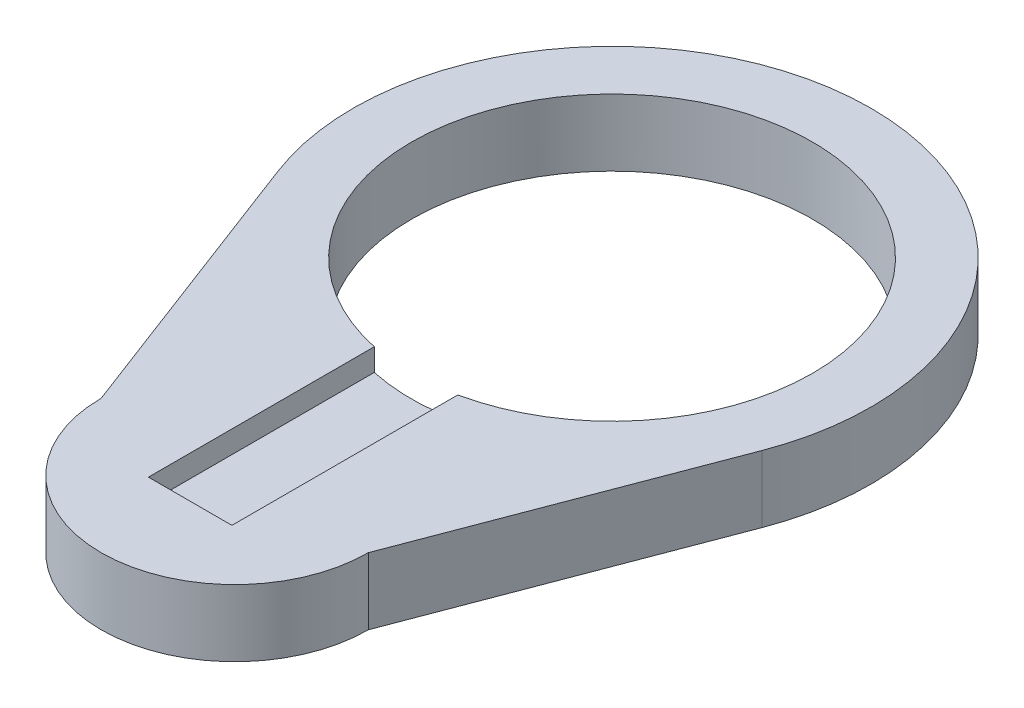
SolidWorks part; units mm, degrees
ref_plane "Front Plane" through (0, 0, 0) normal (0, 0, 1) x (1, 0, 0)
ref_plane "Top Plane" through (0, 0, 0) normal (0, 1, 0) x (1, 0, 0)
ref_plane "Right Plane" through (0, 0, 0) normal (1, 0, 0) x (0, 0, -1)
sketch "Sketch1" plane through (0, 0, 0) normal (0, 1, 0) x (1, 0, 0)
  line L0 (-21.7354, 25.6357) -> (-12, 0)
  line L1 (0, 120.2958) -> (0, -44.3308) construction
  line L2 (21.7354, 25.6357) -> (12, 0)
  arc A0 (-12, 0) -> (12, 0) centre (0, 0) ccw
  circle A1 centre (0, 33.89) radius 18
  arc A2 (21.7354, 25.6357) -> (-21.7354, 25.6357) centre (0, 33.89) ccw
  dimension "D1" = 36
  dimension "D2" = 46.5
  dimension "D3" = 12
  dimension "D4" = 33.89
extrude "Boss-Extrude1" add sketch "Sketch1" along normal blind 6
sketch "Sketch2" plane through (0, 6, 0) normal (0, 1, 0) x (1, 0, 0)
  line L0 (0, 36.2798) -> (0, -14.4492) construction
  line L1 (-3.75, 17) -> (3.75, 17)
  line L2 (-3.75, 17) -> (-3.75, -4)
  line L3 (-3.75, -4) -> (3.75, -4)
  line L4 (3.75, 17) -> (3.75, -4)
  arc A0 (-12, 0) -> (12, 0) centre (0, 0) ccw construction
  arc A1 (-12, 0) -> (12, 0) centre (0, 0) ccw construction
  circle A2 centre (0, 33.89) radius 18 construction
  circle A3 centre (0, 33.89) radius 18 construction
  circle A4 centre (0, 0) radius 3.5 construction
  dimension "D3" = 7
  dimension "D1" = 7.5
  dimension "D2" = 21
  dimension "D4" = 0.5
extrude "Cut-Extrude1" cut sketch "Sketch2" against normal blind 2
